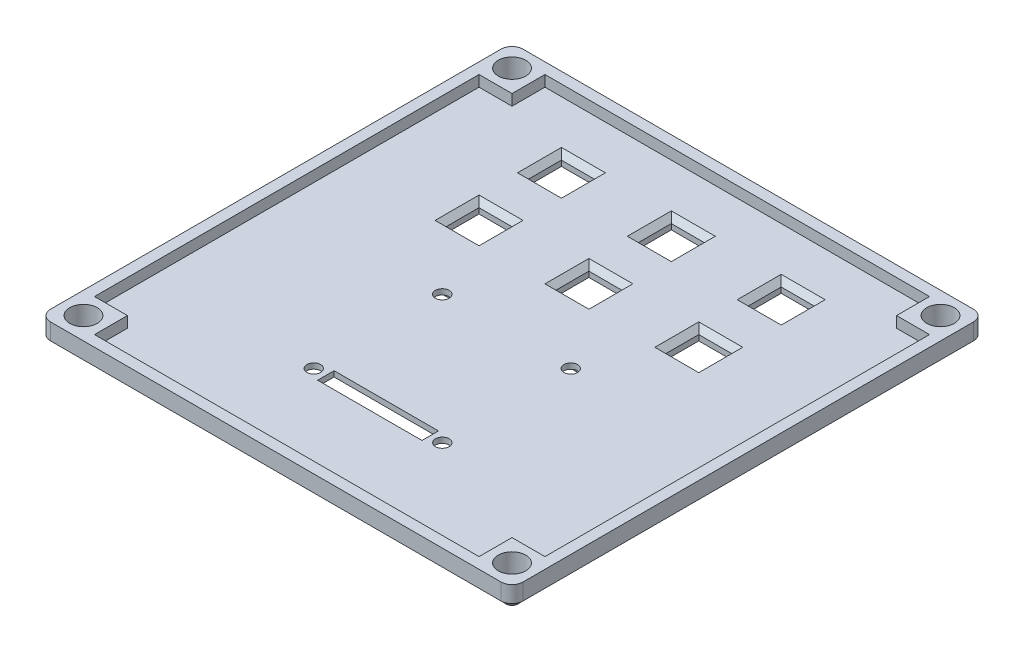
SolidWorks part; units mm, degrees
material "普通碳钢"
ref_plane "前视基准面" through (0, 0, 0) normal (0, 0, 1) x (1, 0, 0)
ref_plane "上视基准面" through (0, 0, 0) normal (0, 1, 0) x (1, 0, 0)
ref_plane "右视基准面" through (0, 0, 0) normal (1, 0, 0) x (0, 0, -1)
sketch "草图2" plane through (0, 0, 0) normal (0, 1, 0) x (1, 0, 0)
  line L1 (-43, -43) -> (43, -43)
  line L2 (-43, -43) -> (-43, 43)
  line L3 (-43, 43) -> (43, 43)
  line L4 (43, -43) -> (43, 43)
  line L5 (-43, -43) -> (43, 43) construction
  line L6 (-43, 43) -> (43, -43) construction
  point P0 (0, 0)
  dimension "D1" = 86
  dimension "D2" = 86
extrude "凸台-拉伸1" add sketch "草图2" along normal blind 2
sketch "草图3" plane through (0, 2, 0) normal (0, 1, 0) x (1, 0, 0)
  line L0 (43, -43) -> (43, 43) construction
  line L1 (-43, -43) -> (43, -43)
  line L2 (-43, -43) -> (-43, 43)
  line L3 (-43, 43) -> (43, 43)
  line L4 (43, -43) -> (43, 43)
  line L5 (-43, -43) -> (43, 43) construction
  line L6 (-43, 43) -> (43, -43) construction
  line L8 (-41, -41) -> (41, -41)
  line L9 (-41, -41) -> (-41, 41)
  line L10 (-41, 41) -> (41, 41)
  line L11 (41, -41) -> (41, 41)
  line L12 (-41, -41) -> (41, 41) construction
  line L13 (-41, 41) -> (41, -41) construction
  point P0 (0, 0)
  point P8 (0, 0)
  dimension "D1" = 82
  dimension "D2" = 82
extrude "凸台-拉伸2" add sketch "草图3" along normal blind 2
sketch "草图4" plane through (0, 0, 41) normal (0, 0, -1) x (-1, 0, 0)
  line L0 (41, 2) -> (-41, 2) construction
  line L1 (-41, 4) -> (-35, 4)
  line L2 (-41, 4) -> (-41, 2)
  line L3 (-41, 2) -> (-35, 2)
  line L4 (-35, 4) -> (-35, 2)
  line L7 (41, 4) -> (35, 4)
  line L8 (41, 4) -> (41, 2)
  line L9 (41, 2) -> (35, 2)
  line L10 (35, 4) -> (35, 2)
  dimension "D1" = 6
  dimension "D2" = 6
  dimension "D3" = 2
  dimension "D4" = 2
extrude "凸台-拉伸3" add sketch "草图4" along normal blind 6
sketch "草图5" plane through (0, 0, -41) normal (0, 0, 1) x (1, 0, 0)
  line L1 (-41, 4) -> (-35, 4)
  line L2 (-41, 4) -> (-41, 2)
  line L3 (-41, 2) -> (-35, 2)
  line L4 (-35, 4) -> (-35, 2)
  line L5 (41, 4) -> (35, 4)
  line L6 (41, 4) -> (41, 2)
  line L7 (41, 2) -> (35, 2)
  line L8 (35, 4) -> (35, 2)
  dimension "D1" = 6
  dimension "D2" = 2
  dimension "D3" = 6
  dimension "D4" = 2
extrude "凸台-拉伸4" add sketch "草图5" along normal blind 6
sketch "草图6" plane through (0, 4, 0) normal (0, 1, 0) x (1, 0, 0)
  line L0 (-43, 43) -> (-43, -43) construction
  line L1 (43, -43) -> (43, 43) construction
  line L2 (43, 43) -> (-43, 43) construction
  line L3 (-43, -43) -> (43, -43) construction
  line L4 (0, 0) -> (0, 29.0211) construction
  line L5 (0, 0) -> (13.175, 0) construction
  circle A0 centre (-39, 39) radius 2.5
  circle A1 centre (39, 39) radius 2.5
  circle A2 centre (39, -39) radius 2.5
  circle A3 centre (-39, -39) radius 2.5
  dimension "D1" = 5
  dimension "D2" = 4
  dimension "D3" = 4
  dimension "D4" = 4
  dimension "D5" = 4
  dimension "D6" = 4
  dimension "D7" = 4
  dimension "D8" = 4
  dimension "D9" = 4
extrude "切除-拉伸1" cut sketch "草图6" against normal through all
fillet "圆角1" radius 2 4 edges at (-43, 2, -43) (-43, 2, 43) (43, 2, 43) (43, 2, -43)
chamfer "倒角1" distance 1 angle 45 8 edges at (0, 0, 43) (43, 0, 0) (0, 0, -43) (42.4142, 0, -42.4142) (42.4142, 0, 42.4142) (-42.4142, 0, -42.4142) (-42.4142, 0, 42.4142) (-43, 0, 0)
sketch "草图7" plane through (0, 0, 0) normal (0, -1, 0) x (1, 0, 0)
  line L0 (-42, 0) -> (42, 0) construction
  line L1 (41, 42) -> (-41, 42) construction
  line L3 (0, 42) -> (0, -42) construction
  line L7 (-14, 27) -> (14, 27)
  line L8 (-14, 27) -> (-14, -1)
  line L9 (-14, -1) -> (14, -1)
  line L10 (14, 27) -> (14, -1)
  point P5 (0, 27)
  dimension "D1" = 28
  dimension "D2" = 28
  dimension "D3" = 15
extrude "切除-拉伸2" cut sketch "草图7" against normal blind 1
sketch "草图8" plane through (0, 1, 0) normal (0, -1, 0) x (1, 0, 0)
  line L0 (14, -1) -> (14, 27) construction
  line L1 (-14, 27) -> (14, 27) construction
  line L2 (-14, 27) -> (-14, 22)
  line L3 (-14, 22) -> (14, 22) construction
  line L4 (14, 27) -> (14, 22) construction
  line L5 (0, 27) -> (0, 0) construction
  line L6 (-11.7, 24.3826) -> (11.7, 24.3826) construction
  line L7 (-9.5, 25.8826) -> (9.5, 25.8826)
  line L8 (-9.5, 25.8826) -> (-9.5, 22.8826)
  line L9 (-9.5, 22.8826) -> (9.5, 22.8826)
  line L10 (9.5, 25.8826) -> (9.5, 22.8826)
  line L11 (-14, 13) -> (14, 13) construction
  line L12 (-14, 27) -> (-14, -1) construction
  line L13 (14, -1) -> (14, 27) construction
  line L14 (-14, -1) -> (14, -1) construction
  circle A0 centre (-11.7, 24.3826) radius 1.25
  circle A1 centre (11.7, 24.3826) radius 1.25
  circle A2 centre (-11.7, 1) radius 1.25
  circle A3 centre (11.7, 1) radius 1.25
  point P10 (0, 25.8826)
  point P21 (-9.5, 24.3826)
  dimension "D3" = 2.5
  dimension "D7" = 2.5
  dimension "D1" = 28
  dimension "D2" = 5
  dimension "D4" = 2.3
  dimension "D5" = 19
  dimension "D6" = 3
  dimension "D8" = 2
extrude "切除-拉伸10" cut sketch "草图8" against normal through all contours A0 | L9 L10 L7 L8 | A1 | A3 | A2
sketch "草图9" plane through (0, 0, 0) normal (0, -1, 0) x (1, 0, 0)
  line L0 (0, -42) -> (0, 42) construction
  line L1 (-3, -11) -> (3, -11)
  line L2 (-3, -11) -> (-3, -17)
  line L3 (-3, -17) -> (3, -17)
  line L4 (3, -11) -> (3, -17)
  line L5 (0, 0) -> (42, 0) construction
  line L6 (-23, -11) -> (-17, -11)
  line L7 (-14, -1) -> (14, -1) construction
  line L8 (17, -11) -> (23, -11)
  line L9 (17, -11) -> (17, -17)
  line L10 (17, -17) -> (23, -17)
  line L11 (23, -11) -> (23, -17)
  line L12 (-3, -11) -> (17, -11) construction
  line L13 (-17, -11) -> (-17, -17)
  line L14 (-23, -17) -> (-17, -17)
  line L15 (-23, -11) -> (-23, -17)
  line L16 (-3, -11) -> (-23, -11) construction
  line L17 (-23, -26) -> (-23, -32)
  line L18 (-23, -26) -> (-17, -26)
  line L19 (-17, -26) -> (-17, -32)
  line L20 (-23, -32) -> (-17, -32)
  line L21 (-3, -32) -> (3, -32)
  line L22 (-3, -26) -> (3, -26)
  line L23 (-3, -26) -> (-3, -32)
  line L24 (3, -26) -> (3, -32)
  line L25 (17, -26) -> (17, -32)
  line L26 (17, -26) -> (23, -26)
  line L27 (23, -26) -> (23, -32)
  line L28 (17, -32) -> (23, -32)
  line L29 (-23, -11) -> (-23, -26) construction
  point P5 (0, -11)
  dimension "D1" = 6
  dimension "D2" = 6
  dimension "D3" = 10
  dimension "D5" = 20
  dimension "D6" = 20
  dimension "D7" = 2
  dimension "D9" = 15
  dimension "D4" = 2
  dimension "D8" = 2
extrude "切除-拉伸11" cut sketch "草图9" against normal through all
chamfer "倒角2" distance 1 angle 45 12 edges at (-23, 2, -29) (-20, 2, -26) (-20, 2, -32) (-17, 2, -29) (-3, 2, -29) (0, 2, -26) (0, 2, -32) (3, 2, -29) (17, 2, -29) (20, 2, -26) (20, 2, -32) (23, 2, -29)
chamfer "倒角3" distance 1 angle 45 12 edges at (-17, 2, -14) (-20, 2, -17) (-23, 2, -14) (-20, 2, -11) (3, 2, -14) (0, 2, -17) (-3, 2, -14) (0, 2, -11) (23, 2, -14) (20, 2, -17) (17, 2, -14) (20, 2, -11)
